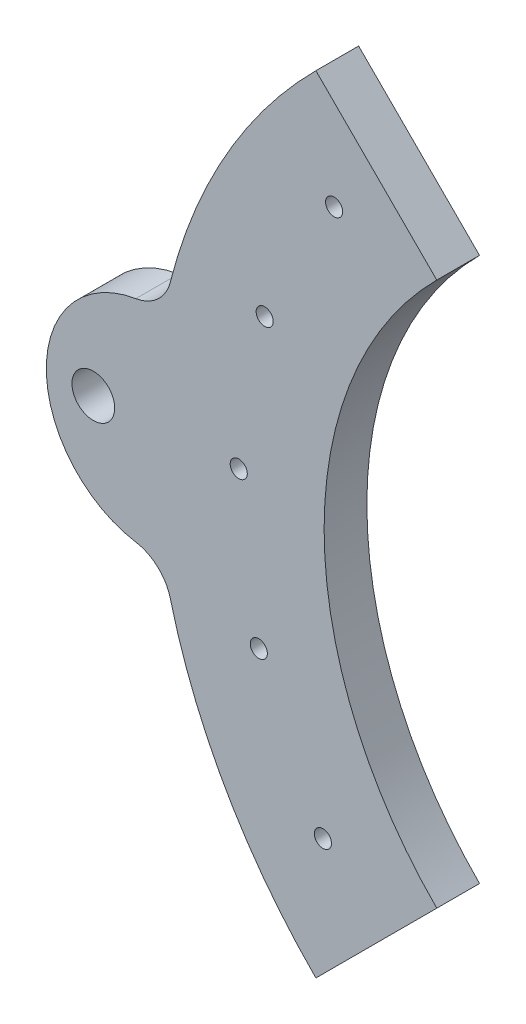
SolidWorks part; units mm, degrees
ref_plane "Front Plane" through (0, 0, 0) normal (0, 0, 1) x (1, 0, 0)
ref_plane "Top Plane" through (0, 0, 0) normal (0, 1, 0) x (1, 0, 0)
ref_plane "Right Plane" through (0, 0, 0) normal (1, 0, 0) x (0, 0, -1)
sketch "Sketch1" plane through (0, 0, 0) normal (0, 0, 1) x (1, 0, 0)
  circle A0 centre (0, 0) radius 130
  circle A1 centre (0, 0) radius 90
  dimension "D1" = 260
  dimension "D2" = 40
sketch "Sketch2" plane through (0, 0, 0) normal (0, 0, 1) x (1, 0, 0)
  line L0 (-130, 47.0552) -> (-130, -55.8624) construction
  line L1 (-63.6396, 63.6396) -> (-91.9239, 91.9239)
  line L2 (-63.6396, -63.6396) -> (-91.9239, -91.9239)
  line L3 (-204.1433, 0) -> (147.6506, 0) construction
  arc A0 (-127.5962, 24.8842) -> (-127.5962, -24.8842) centre (-130, 0) ccw
  circle A2 centre (-144, 0) radius 5
  circle A3 centre (0, 0) radius 130 construction
  circle A4 centre (0, 0) radius 90 construction
  arc A5 (-63.6396, 63.6396) -> (-63.6396, -63.6396) centre (0, 0) ccw
  arc A6 (-91.9239, 91.9239) -> (-127.5962, 24.8842) centre (0, 0) ccw
  arc A7 (-127.5962, -24.8842) -> (-91.9239, -91.9239) centre (0, 0) ccw
  point P6 (-144.7433, 0)
  dimension "D1" = 50
  dimension "D2" = 10
  dimension "D5" = 14
  dimension "D3" = 90
  dimension "D4" = 45
  dimension "D6" = 63.6396
  dimension "D7" = 63.6396
  dimension "D8" = 127.5962
extrude "Boss-Extrude1" add sketch "Sketch2" along normal blind 10
fillet "Fillet1" radius 10 2 edges at (-127.5962, -24.8842, 5) (-127.5962, 24.8842, 5)
sketch "Sketch3" plane through (0, 0, 10) normal (0, 0, 1) x (1, 0, 0)
  line L0 (-63.6396, 63.6396) -> (-91.9239, 91.9239) construction
  circle A0 centre (0, 0) radius 110 construction
  circle A1 centre (-87.6618, 66.4486) radius 2
  circle A2 centre (-103.905, 36.1074) radius 2
  circle A3 centre (-109.9774, 2.2317) radius 2
  circle A4 centre (-105.2843, -31.8624) radius 2
  circle A5 centre (-90.2853, -62.8376) radius 2
  circle A7 centre (-66.4486, -87.6618) radius 2 [skipped]
  point P5 (-77.7817, 77.7817)
  point P21 (0, 0)
  dimension "D1" = 4
  dimension "D2" = 15
  dimension "D3" = 6
extrude "Cut-Extrude1" cut sketch "Sketch3" against normal through all
